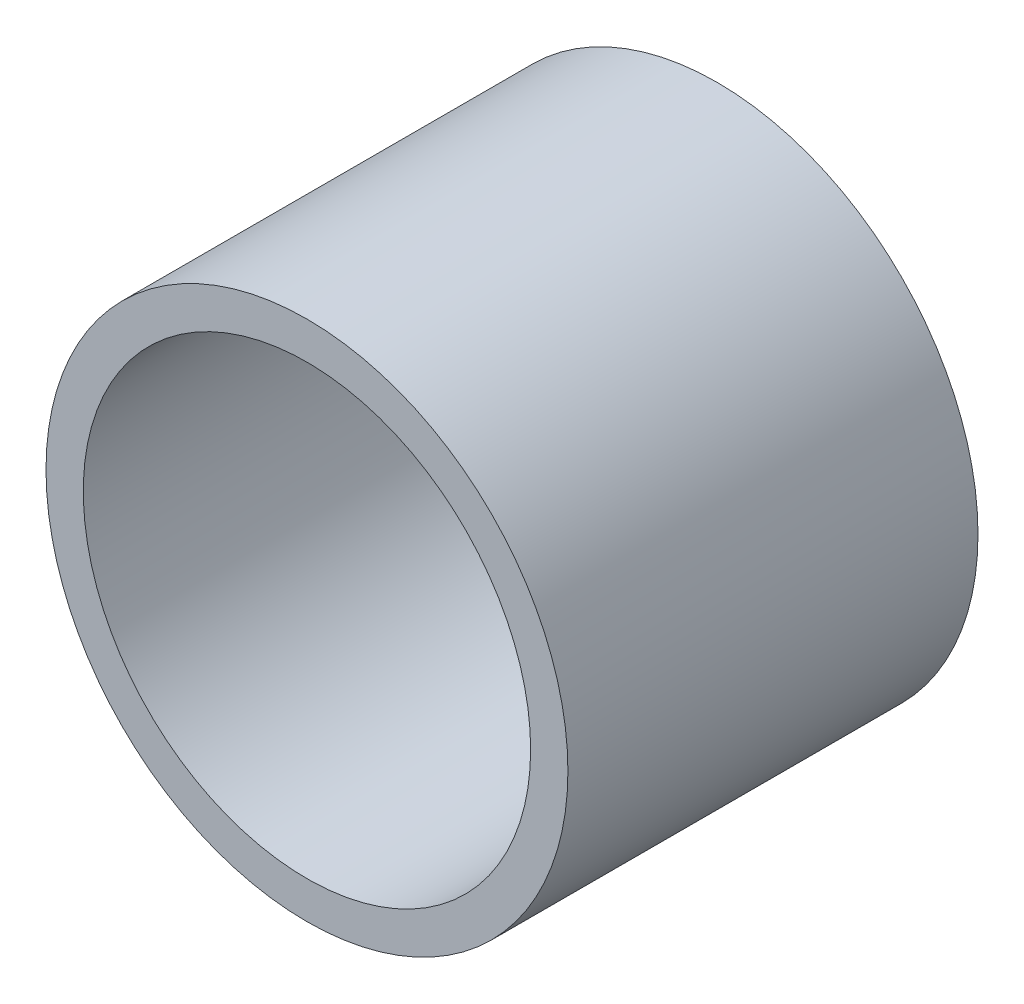
SolidWorks part; units mm, degrees
ref_plane "Front Plane" through (0, 0, 0) normal (0, 0, 1) x (1, 0, 0)
ref_plane "Top Plane" through (0, 0, 0) normal (0, 1, 0) x (1, 0, 0)
ref_plane "Right Plane" through (0, 0, 0) normal (1, 0, 0) x (0, 0, -1)
sketch "Sketch2" plane through (0, 0, 0) normal (0, 0, 1) x (1, 0, 0)
  circle A0 centre (0, 0) radius 35
  dimension "D1" = 70
extrude "Boss-Extrude1" add sketch "Sketch2" along normal mid plane 55
sketch "Sketch3" plane through (0, 0, 27.5) normal (0, 0, 1) x (1, 0, 0)
  circle A0 centre (0, 0) radius 30
  dimension "D1" = 60
extrude "Cut-Extrude1" cut sketch "Sketch3" against normal through all contours A0
